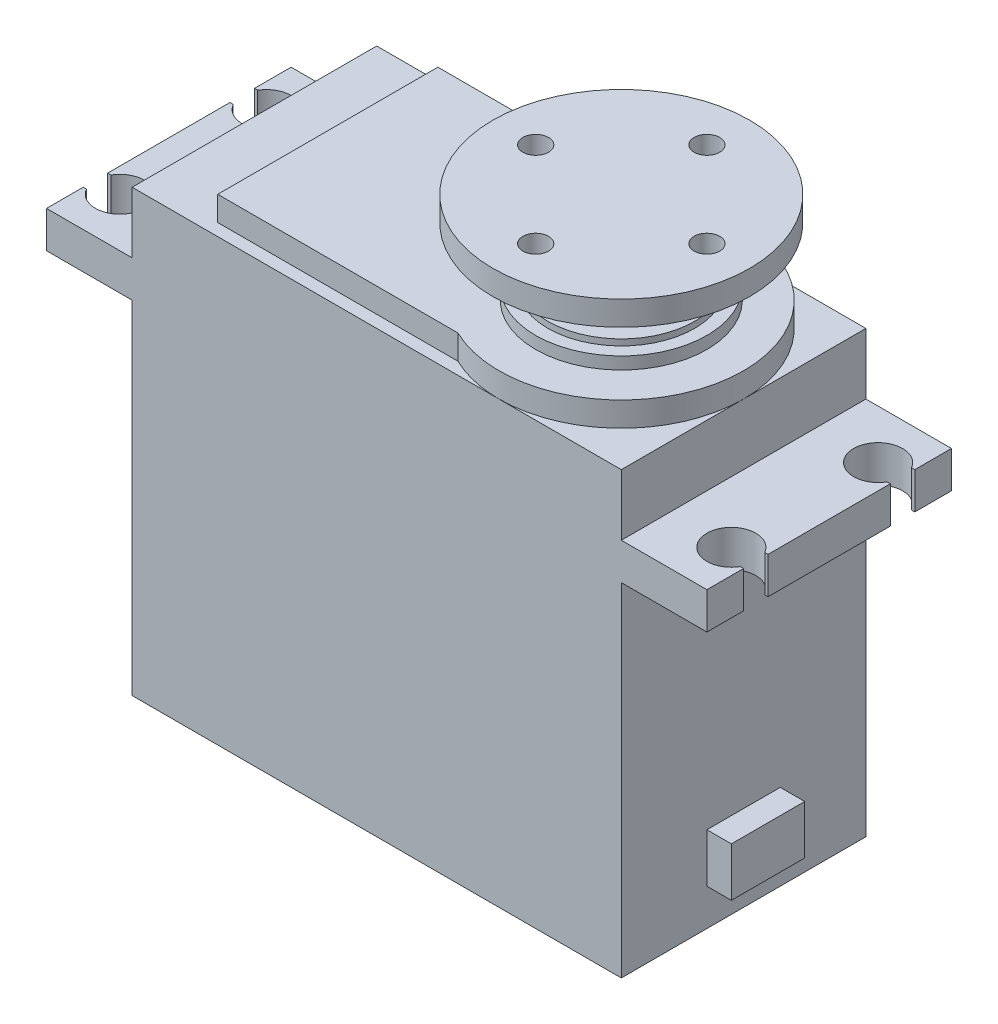
SolidWorks part; units mm, degrees
ref_plane "Front Plane" through (0, 0, 0) normal (0, 0, 1) x (1, 0, 0)
ref_plane "Top Plane" through (0, 0, 0) normal (0, 1, 0) x (1, 0, 0)
ref_plane "Right Plane" through (0, 0, 0) normal (1, 0, 0) x (0, 0, -1)
sketch "Sketch1" plane through (0, 0, 0) normal (0, 0, 1) x (1, 0, 0)
  line L0 (0, 18) -> (0, -18) construction
  line L1 (-20, 18) -> (20, 18)
  line L2 (-20, 18) -> (-20, -18)
  line L3 (-20, -18) -> (20, -18)
  line L4 (20, 18) -> (20, -18)
  line L5 (-20, 0) -> (20, 0) construction
  dimension "D1" = 36
  dimension "D2" = 40
extrude "Boss-Extrude1" add sketch "Sketch1" along normal blind 20
sketch "Sketch2" plane through (0, 18, 0) normal (0, 1, 0) x (1, 0, 0)
  line L0 (20, -20) -> (20, 0) construction
  line L1 (-14, -1) -> (5.6411, -1)
  line L2 (-14, -1) -> (-14, -19)
  line L3 (-14, -19) -> (5.6411, -19)
  line L5 (20, -20) -> (-20, -20) construction
  line L6 (-20, -20) -> (-20, 0) construction
  arc A1 (5.6411, -19) -> (5.6411, -1) centre (10, -10) ccw
  point P8 (10, -10)
  point P11 (20, -10)
  dimension "D3" = 20
  dimension "D1" = 18
  dimension "D2" = 6
  dimension "D4" = 1
extrude "Boss-Extrude3" add sketch "Sketch2" along normal blind 2
sketch "Sketch4" plane through (0, 20, 0) normal (0, 1, 0) x (1, 0, 0)
  line L0 (-14, -1) -> (-14, -19) construction
  circle A0 centre (10, -10) radius 7
  arc A1 (20, -10) -> (10, 0) centre (10, -10) ccw construction
  arc A11 (5.6411, -19) -> (5.6411, -1) centre (10, -10) ccw construction
  point P6 (-14, -10)
  dimension "D1" = 3
  dimension "D2" = 14
extrude "Boss-Extrude4" add sketch "Sketch4" along normal blind 1
sketch "Sketch5" plane through (0, 21, 0) normal (0, 1, 0) x (1, 0, 0)
  line L1 (-14, -1) -> (-14, -19) construction
  circle A0 centre (10, -10) radius 6
  arc A1 (5.6411, -19) -> (5.6411, -1) centre (10, -10) ccw construction
  circle A4 centre (10, -10) radius 7 construction
  point P5 (-14, -10)
  dimension "D1" = 1
  dimension "D2" = 12
extrude "Boss-Extrude5" add sketch "Sketch5" along normal blind 0.5 contours A0
sketch "Sketch8" plane through (0, 21.5, 0) normal (0, 1, 0) x (1, 0, 0)
  circle A0 centre (10, -10) radius 4.5
  circle A1 centre (10, -10) radius 6 construction
  dimension "D1" = 9
extrude "Boss-Extrude6" add sketch "Sketch8" along normal blind 4
sketch "Sketch9" plane through (0, 25.5, 0) normal (0, 1, 0) x (1, 0, 0)
  circle A0 centre (10, -10) radius 10.5
  circle A1 centre (10, -10) radius 4.5 construction
  dimension "D1" = 21
extrude "Boss-Extrude7" add sketch "Sketch9" along normal blind 2 contours A0
sketch "Sketch13" plane through (0, 0, 0) normal (0, 0, -1) x (-1, 0, 0)
  line L0 (-10, 18) -> (20, 18) construction
  line L1 (20, 13) -> (27, 13)
  line L2 (20, 13) -> (20, 10)
  line L3 (20, 10) -> (27, 10)
  line L4 (27, 13) -> (27, 10)
  line L5 (20, 18) -> (20, -18) construction
  line L6 (-27, 13) -> (-20, 13)
  line L7 (-20, -18) -> (-20, 18) construction
  line L8 (-27, 13) -> (-27, 10)
  line L9 (-27, 10) -> (-20, 10)
  line L10 (-20, 13) -> (-20, 10)
  dimension "D1" = 5
  dimension "D2" = 3
  dimension "D3" = 7
extrude "Boss-Extrude8" add sketch "Sketch13" against normal blind 20
sketch "Sketch14" plane through (0, 13, 0) normal (0, 1, 0) x (1, 0, 0)
  line L0 (-27, -10) -> (27, -10) construction
  line L1 (-27, -20) -> (-27, 0) construction
  line L2 (27, -20) -> (27, 0) construction
  line L3 (-27, -17) -> (-27, -15)
  line L4 (10, -20) -> (-20, -20) construction
  line L5 (-1.7482, -20) -> (-1.7482, 0) construction
  line L6 (10, 0) -> (-20, 0) construction
  line L7 (-20, -20) -> (-20, 0) construction
  line L8 (-27, -3) -> (-26.7321, -3)
  line L9 (-27, 0) -> (-20, 0) construction
  line L10 (-27, -3) -> (-27, -5)
  line L11 (-27, -5) -> (-26.7321, -5)
  line L12 (-27, -17) -> (-26.7321, -17)
  line L13 (-27, -15) -> (-26.7321, -15)
  arc A0 (-26.7321, -5) -> (-26.7321, -3) centre (-25, -4) ccw
  arc A1 (-26.7321, -15) -> (-26.7321, -17) centre (-25, -16) cw
  point P10 (-27, -4)
  dimension "D1" = 4
  dimension "D2" = 3
  dimension "D3" = 2
  dimension "D4" = 2
extrude "Cut-Extrude1" cut sketch "Sketch14" against normal blind 3
mirror "Mirror2" about plane through (0, 0, 0) normal (1, 0, 0) of "Cut-Extrude1"
sketch "Sketch17" plane through (20, 0, 0) normal (1, 0, 0) x (0, 0, -1)
  line L0 (-10, -18) -> (-10, 10) construction
  line L1 (-13, -11) -> (-7, -11)
  line L2 (-13, -11) -> (-13, -15)
  line L3 (-13, -15) -> (-7, -15)
  line L4 (-7, -11) -> (-7, -15)
  line L5 (-20, -18) -> (0, -18) construction
  line L6 (-20, 10) -> (0, 10) construction
  point P10 (-10, -15)
  dimension "D1" = 6
  dimension "D2" = 4
  dimension "D3" = 3
extrude "Boss-Extrude9" add sketch "Sketch17" along normal blind 2
sketch "Sketch19" plane through (0, 27.5, 0) normal (0, 1, 0) x (1, 0, 0)
  line L0 (10, 0.5) -> (10, -20.5) construction
  line L1 (-0.5, -10) -> (20.5, -10) construction
  circle A0 centre (10, -10) radius 10.5 construction
  circle A1 centre (10, -3) radius 1.05
  circle A2 centre (3, -10) radius 1.05
  circle A7 centre (10, -17) radius 1.05
  circle A10 centre (17, -10) radius 1.05
  point P14 (10, -10)
  dimension "D1" = 7
  dimension "D2" = 2.1
  dimension "D4" = 2.1
  dimension "D3" = 7
extrude "Cut-Extrude2" cut sketch "Sketch19" against normal blind 2
